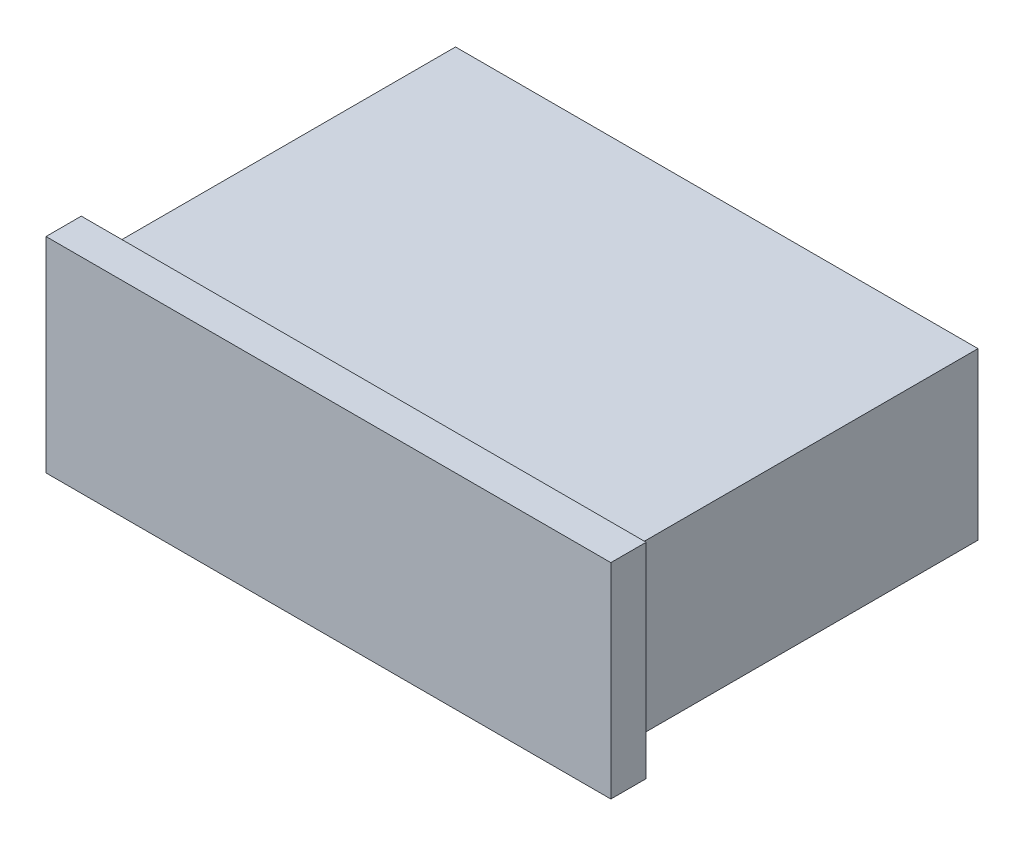
SolidWorks part; units mm, degrees
ref_plane "Front Plane" through (0, 0, 0) normal (0, 0, 1) x (1, 0, 0)
ref_plane "Top Plane" through (0, 0, 0) normal (0, 1, 0) x (1, 0, 0)
ref_plane "Right Plane" through (0, 0, 0) normal (1, 0, 0) x (0, 0, -1)
sketch "Sketch1" plane through (0, 0, 0) normal (0, 0, 1) x (1, 0, 0)
  line L1 (0, 0) -> (7.4, 0)
  line L2 (0, 0) -> (0, 2.35)
  line L3 (0, 2.35) -> (7.4, 2.35)
  line L4 (7.4, 0) -> (7.4, 2.35)
  dimension "D1" = 2.35
  dimension "D2" = 7.4
extrude "Boss-Extrude1" add sketch "Sketch1" along normal blind 5
sketch "Sketch2" plane through (0, 0, 5) normal (0, 0, 1) x (1, 0, 0)
  line L0 (0, 2.35) -> (0, 0) construction
  line L1 (-0.3, -0.275) -> (7.7, -0.275)
  line L2 (-0.3, -0.275) -> (-0.3, 2.625)
  line L3 (-0.3, 2.625) -> (7.7, 2.625)
  line L4 (7.7, -0.275) -> (7.7, 2.625)
  dimension "D1" = 8
  dimension "D2" = 2.9
  dimension "D3" = 0.275
  dimension "D4" = 0.3
extrude "Boss-Extrude2" add sketch "Sketch2" along normal blind 0.5
